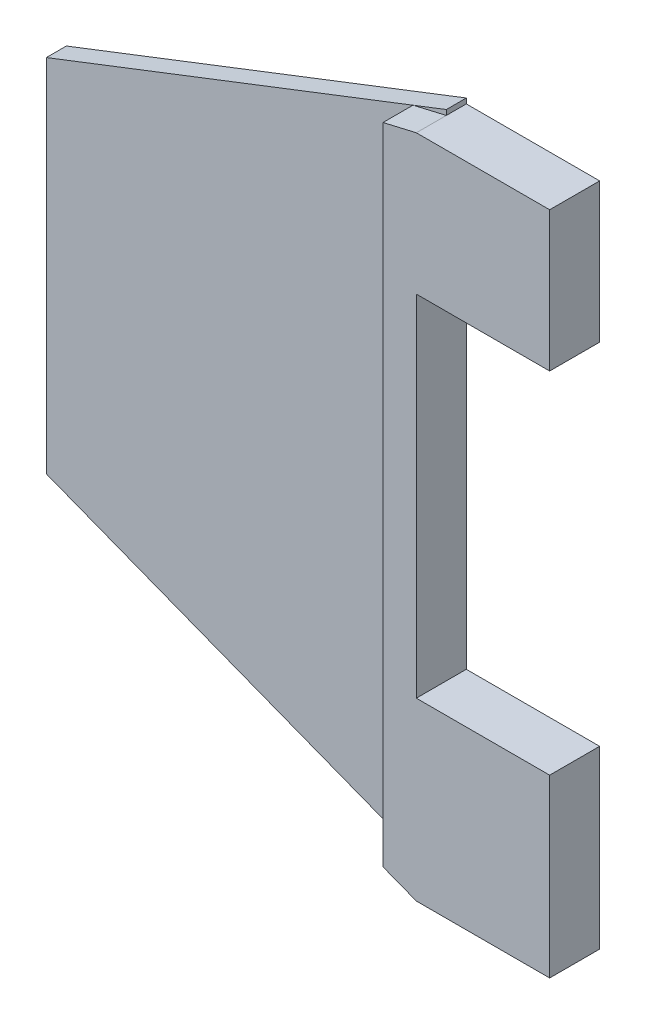
SolidWorks part; units mm, degrees
ref_plane "Спереди" through (0, 0, 0) normal (0, 0, 1) x (1, 0, 0)
ref_plane "Сверху" through (0, 0, 0) normal (0, 1, 0) x (1, 0, 0)
ref_plane "Справа" through (0, 0, 0) normal (1, 0, 0) x (0, 0, -1)
sketch "Sketch1" plane through (0, 0, 0) normal (0, 0, 1) x (1, 0, 0)
  line L0 (0.8669, 10.7989) -> (24.8669, 20.0982)
  line L5 (0.8669, 10.7989) -> (0.8669, -10.8338)
  line L7 (82.9645, -0.0174) -> (-82.9945, -0.0174) construction
  line L8 (24.8669, 20.0982) -> (24.8669, -20.133)
  line L9 (0.8669, -10.8338) -> (24.8669, -20.133)
  point P12 (24.8669, -0.0174)
  dimension "D1" = 24
extrude "Boss-Extrude1" add sketch "Sketch1" along normal blind 1.2 contours L9 L8 L0 L5
sketch "Sketch2" plane through (0, 0, 0) normal (0, 0, -1) x (-1, 0, 0)
  line L5 (-24.8669, 19.7896) -> (-22.8669, 19.3232)
  line L16 (-24.8669, 20.0982) -> (-24.8669, -20.133) construction
  line L25 (-22.8669, 19.3232) -> (-22.8669, -19.3581)
  line L26 (-0.8669, -10.8338) -> (-24.8669, -20.133) construction
  line L27 (-22.8669, -19.3581) -> (-24.8669, -20.133)
  line L28 (-24.8669, -20.133) -> (-32.8669, -20.133)
  line L29 (-32.8669, -20.133) -> (-32.8669, -9.592)
  line L30 (-32.8669, 19.7896) -> (-24.8669, 19.7896)
  line L31 (-0.8669, 10.7989) -> (-24.8669, 20.0982) construction
  line L32 (-32.8669, 11.408) -> (-32.8669, 19.7896)
  line L33 (-32.8669, -9.592) -> (-24.8669, -9.592)
  line L35 (-32.8669, 11.408) -> (-24.8669, 11.408)
  line L36 (-24.8669, -9.592) -> (-24.8669, 11.408)
  dimension "D1" = 2
  dimension "D2" = 21
  dimension "D3" = 0
  dimension "D4" = 10
extrude "Boss-Extrude2" add sketch "Sketch2" against normal blind 3
